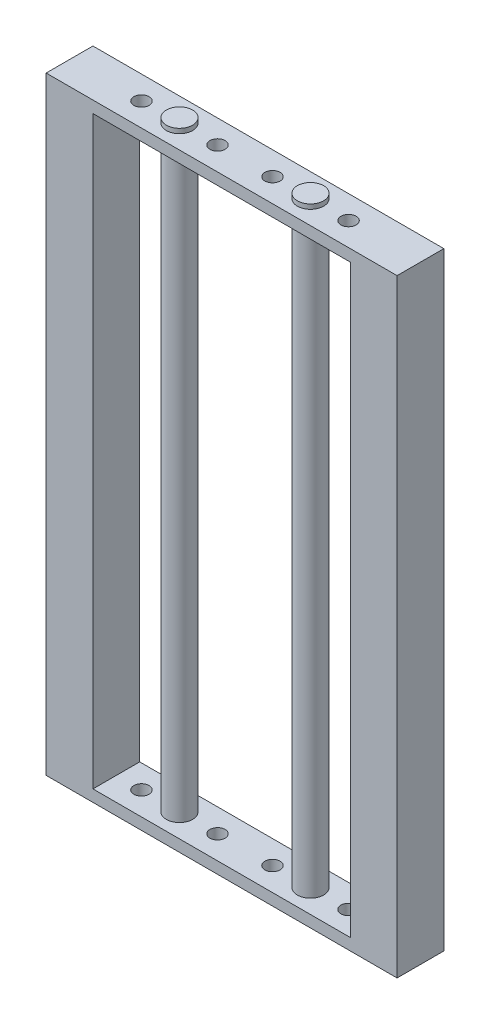
SolidWorks part; units mm, degrees
ref_plane "Front Plane" through (0, 0, 0) normal (0, 0, 1) x (1, 0, 0)
ref_plane "Top Plane" through (0, 0, 0) normal (0, 1, 0) x (1, 0, 0)
ref_plane "Right Plane" through (0, 0, 0) normal (1, 0, 0) x (0, 0, -1)
sketch "Sketch1" plane through (0, 0, 0) normal (0, 0, 1) x (1, 0, 0)
  line L0 (0, 262.7825) -> (0, 125) construction
  line L1 (-200.2495, 0) -> (418.6194, 0) construction
  line L2 (-55, -105) -> (-55, 105)
  line L4 (-75, -125) -> (-75, 125)
  line L6 (75, -125) -> (75, 125)
  line L7 (-75, -125) -> (75, 125) construction
  line L8 (-75, 125) -> (75, -125) construction
  line L10 (55, -105) -> (55, 105)
  line L12 (55, 105) -> (55, 125)
  line L13 (-55, 105) -> (-55, 125)
  line L14 (-55, -105) -> (-55, -125)
  line L15 (55, -105) -> (55, -125)
  line L16 (-55, -105) -> (55, -105) construction
  line L17 (0, -125) -> (0, -394.6857) construction
  line L18 (-55, 105) -> (55, 105) construction
  line L19 (0, 0) -> (0, -105) construction
  line L21 (-75, 125) -> (75, 125) construction
  line L23 (-75, -125) -> (75, -125) construction
  line L24 (-63.3569, 130) -> (-75, 130)
  line L25 (55, 125) -> (-55, 125)
  line L26 (75, 125) -> (75, 130)
  line L27 (75, 130) -> (-63.3569, 130)
  line L28 (-75, 125) -> (-75, 130)
  line L30 (55, -125) -> (-55, -125)
  line L31 (75, -125) -> (75, -130)
  line L32 (75, -130) -> (-75, -130)
  line L33 (-75, -125) -> (-75, -130)
  point P5 (0, 0)
  dimension "D1" = 250
  dimension "D2" = 150
  dimension "D4" = 5
  dimension "D3" = 210
  dimension "D5" = 5
extrude "Boss-Extrude1" add sketch "Sketch1" along normal blind 20
sketch "Sketch2" plane through (0, -130, 0) normal (0, -1, 0) x (1, 0, 0)
  line L0 (0, 0) -> (0, 33.0381) construction
  line L1 (-75, 0) -> (75, 0) construction
  line L2 (-75, 20) -> (-75, 0) construction
  circle A0 centre (-28, 10) radius 5.6125
  circle A1 centre (28, 10) radius 5.6125
  dimension "D1" = 47
extrude "Boss-Extrude2" add sketch "Sketch2" against normal blind 262
sketch "Sketch3" plane through (0, 125, 0) normal (0, -1, 0) x (1, 0, 0)
  circle A0 centre (-44.25, 10) radius 3.25
  circle A1 centre (-11.75, 10) radius 3.25
  circle A2 centre (11.75, 10) radius 3.25
  circle A3 centre (44.25, 10) radius 3.25
extrude "Cut-Extrude1" cut sketch "Sketch3" against normal blind 10
sketch "Sketch4" plane through (0, -130, 0) normal (0, -1, 0) x (1, 0, 0)
  circle A0 centre (-44.25, 10) radius 3.25
  circle A1 centre (-11.75, 10) radius 3.25
  circle A2 centre (11.75, 10) radius 3.25
  circle A3 centre (44.25, 10) radius 3.25
extrude "Cut-Extrude2" cut sketch "Sketch4" against normal blind 10
